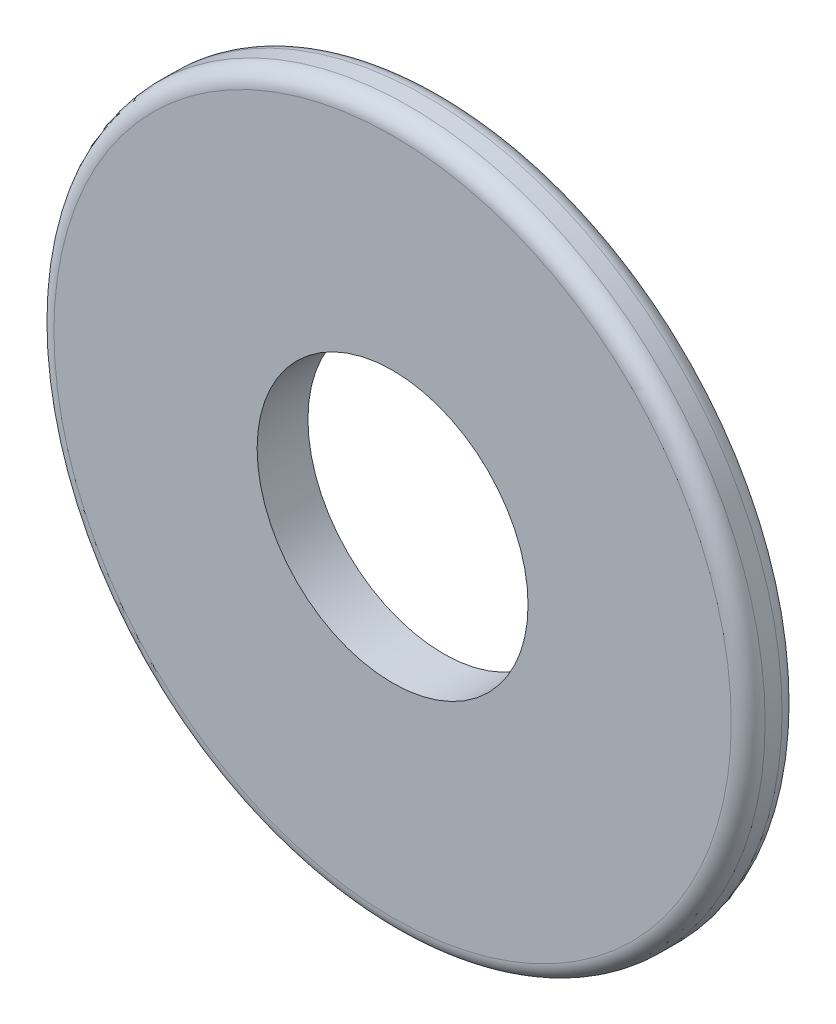
SolidWorks part; units mm, degrees
ref_plane "Front Plane" through (0, 0, 0) normal (0, 0, 1) x (1, 0, 0)
ref_plane "Top Plane" through (0, 0, 0) normal (0, 1, 0) x (1, 0, 0)
ref_plane "Right Plane" through (0, 0, 0) normal (1, 0, 0) x (0, 0, -1)
sketch "Sketch1" plane through (0, 0, 0) normal (0, 0, 1) x (1, 0, 0)
  circle A0 centre (0, 0) radius 4
  circle A1 centre (0, 0) radius 10.5
  dimension "D1" = 8
  dimension "D2" = 21
extrude "Boss-Extrude1" add sketch "Sketch1" along normal blind 1.5
fillet "Fillet1" radius 0.5 2 edges at (10.5, 0, 0) (10.5, 0, 1.5)
